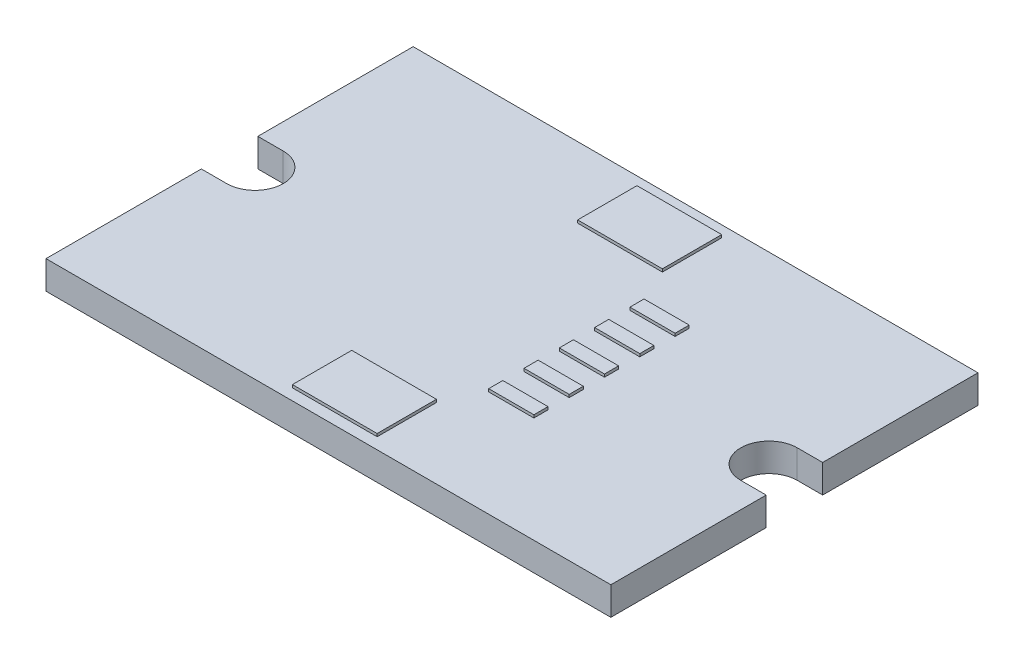
SolidWorks part; units mm, degrees
ref_plane "Front" through (0, 0, 0) normal (0, 0, 1) x (1, 0, 0)
ref_plane "Top" through (0, 0, 0) normal (0, 1, 0) x (1, 0, 0)
ref_plane "Right" through (0, 0, 0) normal (1, 0, 0) x (0, 0, -1)
sketch "Sketch1" plane through (0, 0, 0) normal (0, 1, 0) x (1, 0, 0)
  line L0 (-10, -6.5) -> (10, 6.5) construction
  line L1 (-10, 6.5) -> (10, 6.5)
  line L2 (-10, 6.5) -> (-10, 1)
  line L3 (-10, -6.5) -> (10, -6.5)
  line L4 (10, 6.5) -> (10, 1)
  line L5 (-11.2714, 0) -> (11.6235, 0) construction
  line L6 (10, 1) -> (9.1, 1)
  line L7 (9.1, -1) -> (10, -1)
  line L8 (10, -1) -> (10, -6.5)
  line L9 (0, 6.5) -> (0, 0) construction
  line L10 (-10, 1) -> (-9.1, 1)
  line L11 (-9.1, -1) -> (-10, -1)
  line L12 (-10, -1) -> (-10, -6.5)
  arc A0 (9.1, 1) -> (9.1, -1) centre (9.1, 0) ccw
  arc A1 (-9.1, 1) -> (-9.1, -1) centre (-9.1, 0) cw
  dimension "D3" = 1
  dimension "D1" = 13
  dimension "D2" = 20
  dimension "D4" = 0.9
extrude "Boss-Extrude1" add sketch "Sketch1" along normal blind 1
sketch "Sketch2" plane through (0, 1, 0) normal (0, 1, 0) x (1, 0, 0)
  line L0 (-3.6243, 0) -> (0, 0) construction
  line L1 (0, 0) -> (0, 5.3358) construction
  line L3 (-2.5, -5.2752) -> (-2.5, 5.3358) construction
  line L5 (3.525, -2.5) -> (1.925, -2.5) construction
  line L6 (-1.675, -6.1) -> (1.325, -6.1)
  line L7 (-1.675, -6.1) -> (-1.675, -4)
  line L8 (-1.675, -4) -> (1.325, -4)
  line L9 (1.325, -6.1) -> (1.325, -4)
  line L10 (1.925, -2.75) -> (3.525, -2.75)
  line L11 (1.925, -2.75) -> (1.925, -2.25)
  line L12 (1.925, -2.25) -> (3.525, -2.25)
  line L13 (3.525, -2.75) -> (3.525, -2.25)
  line L14 (1.925, -1.5) -> (1.925, -1)
  line L15 (1.925, -1.5) -> (3.525, -1.5)
  line L16 (3.525, -1.5) -> (3.525, -1)
  line L17 (1.925, -1) -> (3.525, -1)
  line L18 (1.925, -0.25) -> (1.925, 0.25)
  line L19 (1.925, -0.25) -> (3.525, -0.25)
  line L20 (3.525, -0.25) -> (3.525, 0.25)
  line L21 (1.925, 0.25) -> (3.525, 0.25)
  line L22 (1.925, 1) -> (1.925, 1.5)
  line L23 (1.925, 1) -> (3.525, 1)
  line L24 (3.525, 1) -> (3.525, 1.5)
  line L25 (1.925, 1.5) -> (3.525, 1.5)
  line L26 (1.925, 2.25) -> (1.925, 2.75)
  line L27 (1.925, 2.25) -> (3.525, 2.25)
  line L28 (3.525, 2.25) -> (3.525, 2.75)
  line L29 (1.925, 2.75) -> (3.525, 2.75)
  line L30 (-1.675, 6.1) -> (-1.675, 4)
  line L31 (-1.675, 6.1) -> (1.325, 6.1)
  line L32 (1.325, 6.1) -> (1.325, 4)
  line L33 (-1.675, 4) -> (1.325, 4)
  dimension "D1" = 3
  dimension "D2" = 2.5
  dimension "D3" = 2.1
  dimension "D4" = 0.6
  dimension "D5" = 0.5
  dimension "D6" = 1.5
  dimension "D7" = 1.6
  dimension "D9" = 5.5
  dimension "D10" = 0.825
  dimension "D8" = 5
extrude "Boss-Extrude2" add sketch "Sketch2" along normal blind 0.1
